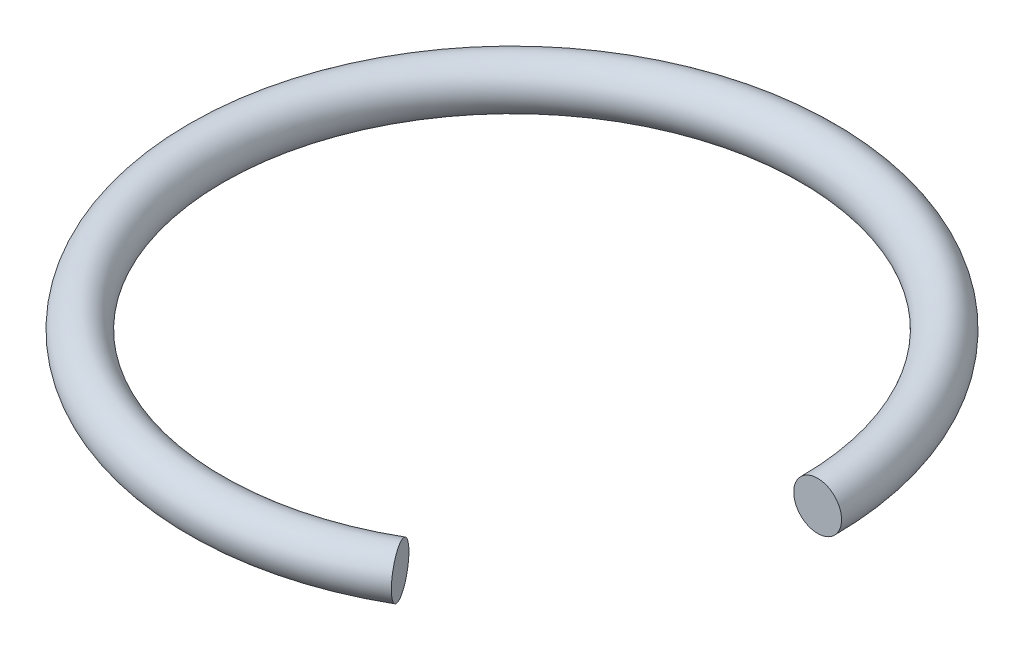
SolidWorks part; units mm, degrees
ref_plane "Front Plane" through (0, 0, 0) normal (0, 0, 1) x (1, 0, 0)
ref_plane "Top Plane" through (0, 0, 0) normal (0, 1, 0) x (1, 0, 0)
ref_plane "Right Plane" through (0, 0, 0) normal (1, 0, 0) x (0, 0, -1)
sketch "Reconstructed nominal axial profile" plane through (0, 0, 0) normal (0, 0, 1) x (1, 0, 0)
  line L0 (0, -500) -> (0, 50) construction
  circle A0 centre (2.3, 0) radius 0.18
revolve "Native revolved geometry" add sketch "Reconstructed nominal axial profile" angle 300 about L0
